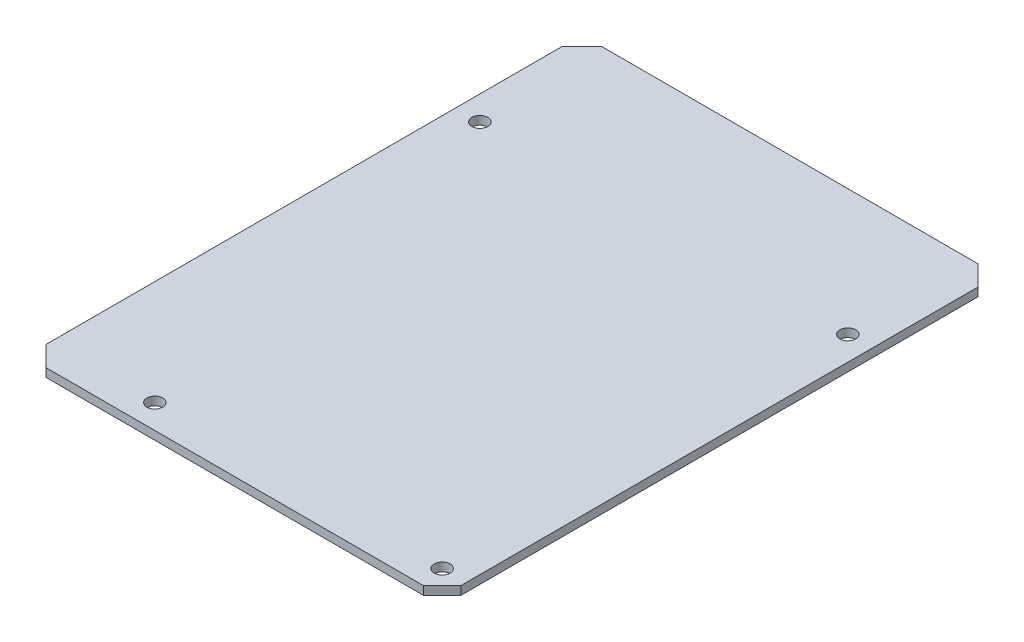
SolidWorks part; units mm, degrees
material "Circuit imprimé de calcul, complexe"
ref_plane "Plan de face" through (0, 0, 0) normal (0, 0, 1) x (1, 0, 0)
ref_plane "Plan de dessus" through (0, 0, 0) normal (0, 1, 0) x (1, 0, 0)
ref_plane "Plan de droite" through (0, 0, 0) normal (1, 0, 0) x (0, 0, -1)
sketch "Repères" plane through (0, 0, 0) normal (0, 1, 0) x (1, 0, 0)
  line L0 (-35.56, 52.58) -> (-39.37, 48.77)
  line L1 (-34.79, 28.702) -> (34.81, 28.702) construction
  line L2 (-34.79, 28.702) -> (-34.79, -48.008) construction
  line L3 (-34.79, -48.008) -> (34.81, -48.008) construction
  line L4 (34.81, 28.702) -> (34.81, -48.008) construction
  line L7 (-35.56, 52.58) -> (35.56, 52.58)
  line L8 (-39.37, 48.77) -> (-39.37, -48.77)
  line L9 (-35.56, -52.58) -> (35.814, -52.58)
  line L10 (39.37, 48.77) -> (39.37, -49.024)
  line L11 (-39.37, 52.58) -> (39.37, -52.58) construction
  line L12 (-39.37, -52.58) -> (39.37, 52.58) construction
  line L13 (35.56, 52.58) -> (39.37, 48.77)
  line L14 (39.37, -49.024) -> (35.814, -52.58)
  line L15 (-39.37, -48.77) -> (-35.56, -52.58)
  circle A0 centre (-34.79, 28.702) radius 1.5
  circle A1 centre (34.81, 28.702) radius 1.5
  circle A4 centre (34.81, -48.008) radius 1.5
  circle A5 centre (-19.55, -48.008) radius 1.5
  point P0 (0, 0)
  point P10 (0, 0)
  dimension "D1" = 3
  dimension "D2" = 69.6
  dimension "D3" = 76.71
  dimension "D4" = 78.74
  dimension "D5" = 105.16
  dimension "D6" = 4.572
  dimension "D7" = 4.58
  dimension "D12" = 15.24
extrude "CI" add sketch "Repères" along normal blind 1.6
